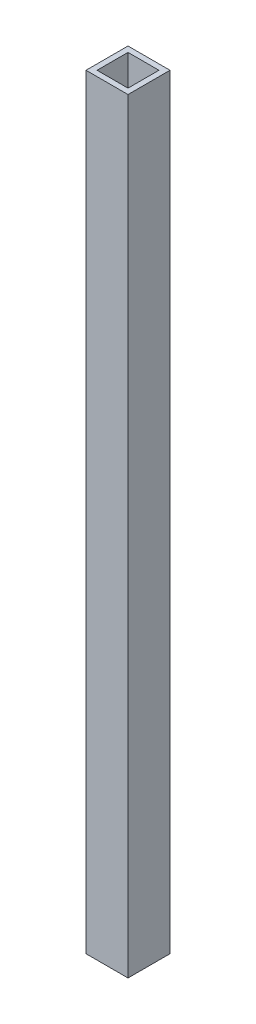
SolidWorks part; units mm, degrees
material "Plain Carbon Steel"
ref_plane "Front Plane" through (0, 0, 0) normal (0, 0, 1) x (1, 0, 0)
ref_plane "Top Plane" through (0, 0, 0) normal (0, 1, 0) x (1, 0, 0)
ref_plane "Right Plane" through (0, 0, 0) normal (1, 0, 0) x (0, 0, -1)
sketch "Sketch1" plane through (0, 0, 0) normal (0, 1, 0) x (1, 0, 0)
  line L0 (5, 33) -> (33, 33)
  line L1 (0, 0) -> (38, 0)
  line L2 (0, 0) -> (0, 38)
  line L3 (0, 38) -> (38, 38)
  line L4 (38, 0) -> (38, 38)
  line L5 (33, 5) -> (33, 33)
  line L6 (5, 5) -> (33, 5)
  line L7 (5, 5) -> (5, 33)
  dimension "D1" = 38
  dimension "D2" = 38
  dimension "D3" = 5
extrude "Boss-Extrude1" add sketch "Sketch1" along normal blind 692
